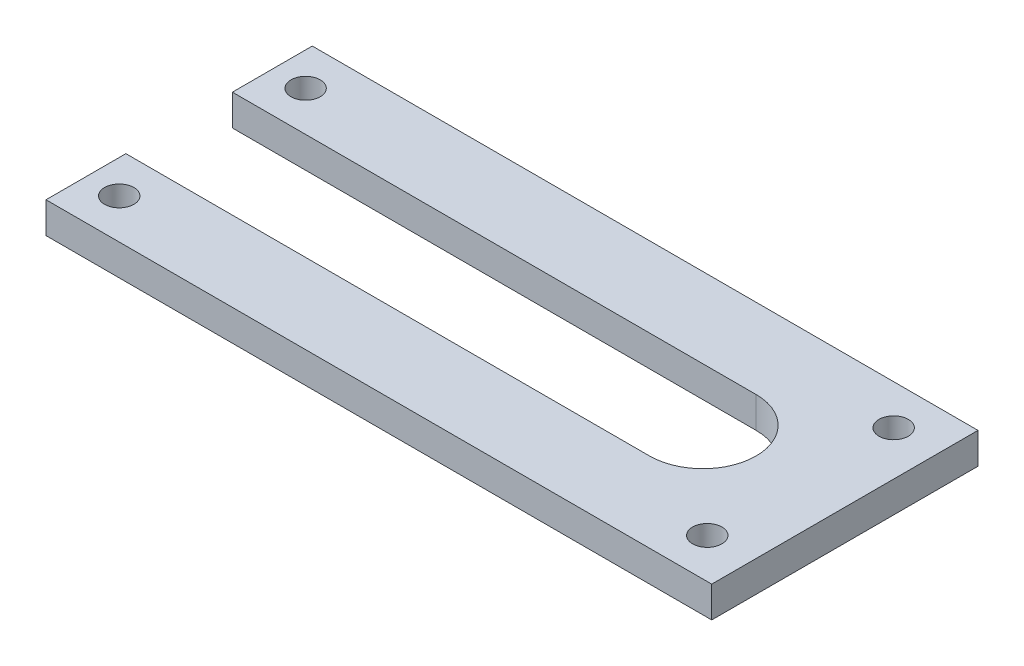
SolidWorks part; units mm, degrees
ref_plane "Piano frontale" through (0, 0, 0) normal (0, 0, 1) x (1, 0, 0)
ref_plane "Piano superiore" through (0, 0, 0) normal (0, 1, 0) x (1, 0, 0)
ref_plane "Piano destro" through (0, 0, 0) normal (1, 0, 0) x (0, 0, -1)
sketch "Schizzo1" plane through (0, 0, 0) normal (0, 0, 1) x (1, 0, 0)
  line L0 (657.3639, 1138.1786) -> (3286.8194, 1138.1786) construction
  line L1 (0, 0) -> (150, 0)
  line L2 (150, 0) -> (150, 7)
  line L3 (150, 7) -> (0, 7)
  line L4 (0, 7) -> (0, 0)
  dimension "D1" = 150
  dimension "D2" = 7
extrude "Estrusione-Estrusione1" add sketch "Schizzo1" against normal blind 80
sketch "Schizzo2" plane through (0, 0, 0) normal (0, 1, 0) x (1, 0, 0)
  line L0 (85.8333, 29.5335) -> (333.8638, 29.5335) construction
  line L1 (85.8333, 102.5) -> (429.1667, 102.5) construction
  line L2 (0, 0) -> (0, 18)
  line L3 (0, 80) -> (0, 0) construction
  line L4 (0, 60) -> (150, 60)
  line L5 (150, 80) -> (150, 0) construction
  line L6 (150, 60) -> (150, 0)
  line L7 (150, 0) -> (0, 0)
  line L8 (0, 30) -> (150, 30) construction
  line L9 (0, 18) -> (118, 18)
  line L10 (0, 42) -> (118, 42)
  line L11 (118, 46.6294) -> (118, -4.7929) construction
  line L12 (0, 18) -> (150, 18) construction
  line L13 (0, 42) -> (150, 42) construction
  line L14 (140, 63.3143) -> (140, -10.7232) construction
  line L15 (0, 42) -> (0, 60)
  line L16 (-28.7018, 97.8291) -> (174.8691, 97.8291)
  line L17 (-28.7018, 97.8291) -> (-28.7018, -40.845)
  line L18 (-28.7018, -40.845) -> (174.8691, -40.845)
  line L19 (174.8691, 97.8291) -> (174.8691, -40.845)
  line L20 (140, 51) -> (-34.5064, 51) construction
  arc A0 (118, 18) -> (118, 42) centre (118, 30) ccw
  circle A1 centre (140, 51) radius 3.3
  circle A2 centre (140, 9) radius 3.3
  circle A3 centre (7.5, 51) radius 3.3
  circle A4 centre (7.5, 9) radius 3.3
  dimension "D3" = 32
  dimension "D6" = 6.6
  dimension "D7" = 6.6
  dimension "D1" = 60
  dimension "D2" = 24
  dimension "D4" = 10
  dimension "D5" = 9
  dimension "D8" = 7.5
extrude "Taglio-Estrusione1" cut sketch "Schizzo2" along normal through all contours L19 L16 L17 L18 L9 A0 L10 L15 L4 L6 L7 L2 | A2 | A1 | A4 | A3
